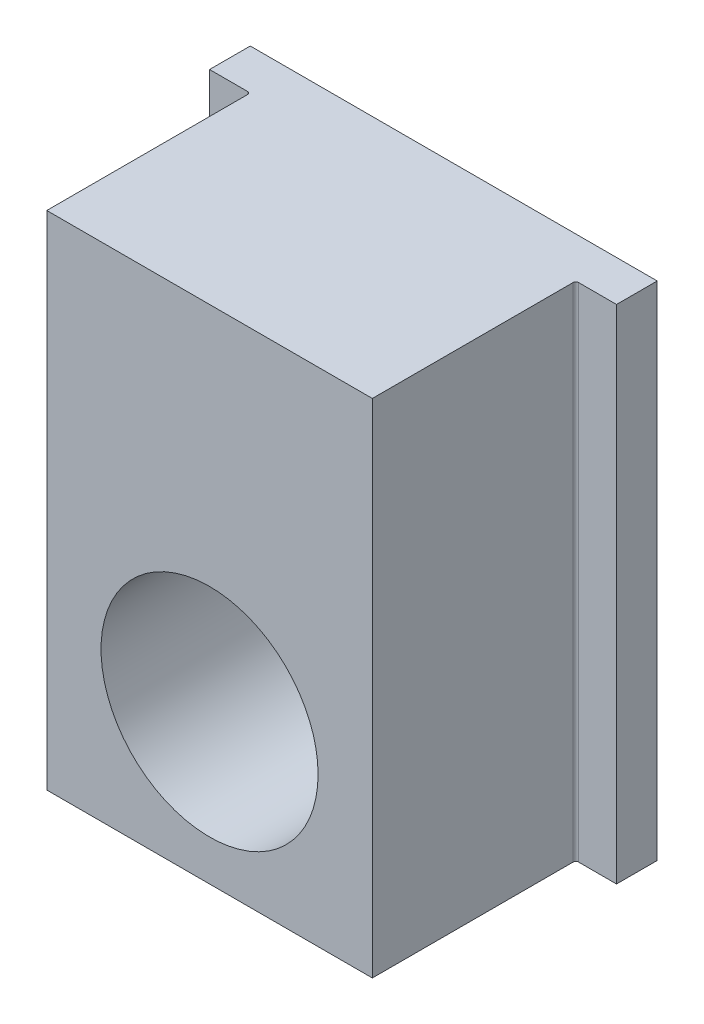
SolidWorks part; units mm, degrees
ref_plane "Piano frontale" through (0, 0, 0) normal (0, 0, 1) x (1, 0, 0)
ref_plane "Piano superiore" through (0, 0, 0) normal (0, 1, 0) x (1, 0, 0)
ref_plane "Piano destro" through (0, 0, 0) normal (1, 0, 0) x (0, 0, -1)
sketch "Schizzo1" plane through (0, 0, 0) normal (0, 1, 0) x (1, 0, 0)
  line L0 (-15, 0) -> (15, 0)
  line L1 (15, 0) -> (15, -3)
  line L2 (15, -3) -> (12, -3)
  line L3 (12, -3) -> (12, -18)
  line L4 (12, -18) -> (-12, -18)
  line L5 (-12, -18) -> (-12, -3)
  line L6 (-12, -3) -> (-15, -3)
  line L7 (-15, -3) -> (-15, 0)
  line L8 (0, 0) -> (0, -30.0991) construction
  dimension "D1" = 30
  dimension "D2" = 24
  dimension "D3" = 3
  dimension "D4" = 15
extrude "Estrusione-Estrusione1" add sketch "Schizzo1" along normal blind 37 contours L4 L5 L6 L7 L0 L1 L2 L3
sketch "Schizzo4" plane through (0, 0, 18) normal (0, 0, 1) x (1, 0, 0)
  line L0 (0, 11) -> (0, 0) construction
  line L1 (12, 0) -> (-12, 0) construction
  circle A0 centre (0, 11) radius 8
  dimension "D1" = 16
  dimension "D2" = 11
extrude "Taglio-Estrusione1" cut sketch "Schizzo4" against normal through all
fillet "Raccordo1" radius 0.2 2 edges at (-12, 18.5, 3) (12, 18.5, 3)
